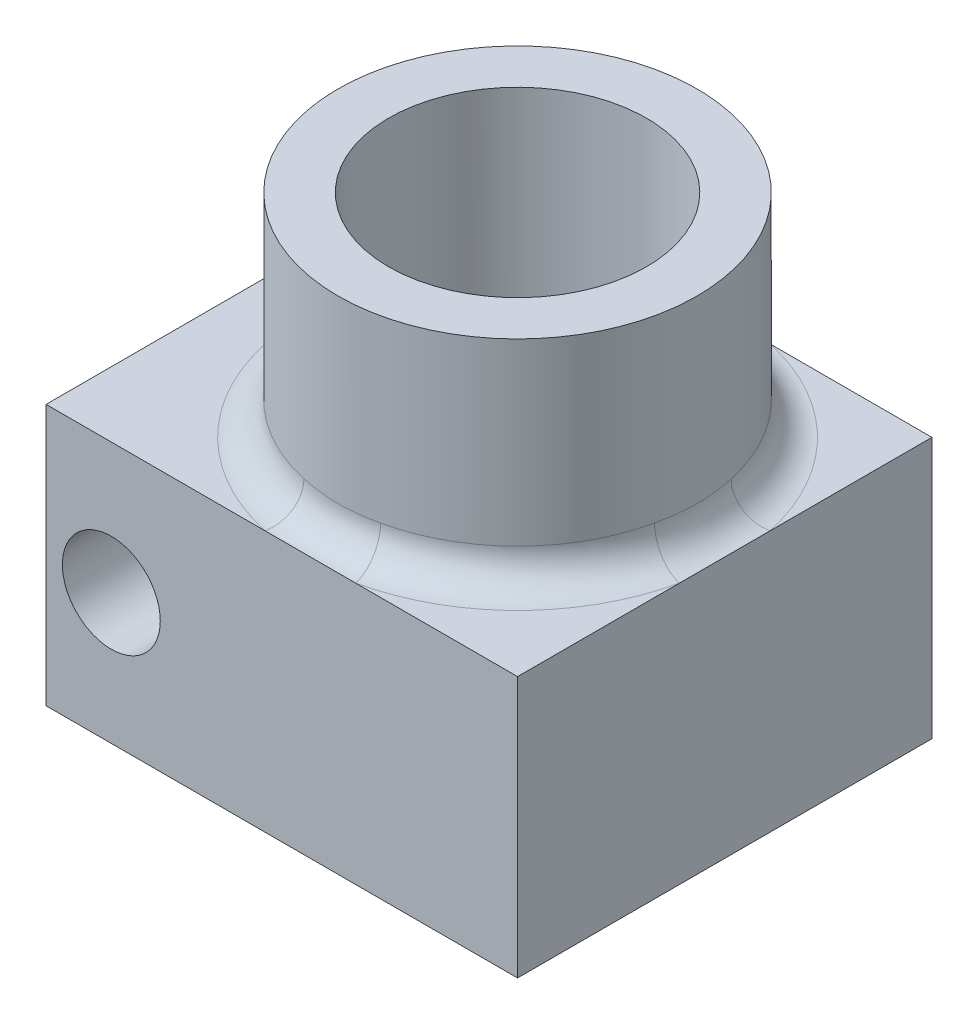
SolidWorks part; units mm, degrees
material "AISI 1020"
ref_plane "Front Plane" through (0, 0, 0) normal (0, 0, 1) x (1, 0, 0)
ref_plane "Top Plane" through (0, 0, 0) normal (0, 1, 0) x (1, 0, 0)
ref_plane "Right Plane" through (0, 0, 0) normal (1, 0, 0) x (0, 0, -1)
sketch "Sketch1" plane through (0, 0, 0) normal (0, 1, 0) x (1, 0, 0)
  line L0 (4.053, -4.2372) -> (-8.647, -4.2372) construction
  line L2 (-8.647, 8.4628) -> (16.753, 8.4628)
  line L4 (16.753, -16.9372) -> (-8.647, -16.9372)
  line L6 (-8.647, -16.9372) -> (-10.397, -16.9372)
  line L8 (-10.397, 8.4628) -> (-8.647, 8.4628)
  line L12 (16.753, 8.4628) -> (16.753, -16.9372)
  line L13 (-10.397, -16.9372) -> (-12.147, -16.9372)
  line L14 (-12.147, -16.9372) -> (-12.147, 8.4628)
  line L15 (-12.147, 8.4628) -> (-10.397, 8.4628)
  arc A0 (1.7659, 3.3245) -> (1.8335, 2.4017) centre (3.6444, 2.9983) ccw
  arc A1 (1.8335, 2.4017) -> (1.4858, 2.2751) centre (4.053, -4.2372) ccw
  arc A2 (1.4858, 2.2751) -> (0.9444, 3.0255) centre (-0.285, 1.5682) ccw
  arc A3 (0.9444, 3.0255) -> (0.4875, 2.8125) centre (4.053, -4.2372) ccw
  arc A4 (0.4875, 2.8125) -> (0.7144, 1.9154) centre (2.3942, 2.8175) ccw
  arc A5 (0.7144, 1.9154) -> (0.3939, 1.7304) centre (4.053, -4.2372) ccw
  arc A6 (0.3939, 1.7304) -> (-0.2695, 2.3754) centre (-1.2272, 0.7267) ccw
  arc A7 (-0.2695, 2.3754) -> (-0.6825, 2.0863) centre (4.053, -4.2372) ccw
  arc A8 (-0.6825, 2.0863) -> (-0.3032, 1.2422) centre (1.1944, 2.4223) ccw
  arc A9 (-0.3032, 1.2422) -> (-0.5867, 1.0043) centre (4.053, -4.2372) ccw
  arc A10 (-0.5867, 1.0043) -> (-1.3521, 1.5243) centre (-2.0089, -0.2656) ccw
  arc A11 (-1.3521, 1.5243) -> (-1.7086, 1.1679) centre (4.053, -4.2372) ccw
  arc A12 (-1.7086, 1.1679) -> (-1.1885, 0.4025) centre (0.0814, 1.8247) ccw
  arc A13 (-1.1885, 0.4025) -> (-1.4264, 0.119) centre (4.053, -4.2372) ccw
  arc A14 (-1.4264, 0.119) -> (-2.2705, 0.4982) centre (-2.6065, -1.3786) ccw
  arc A15 (-2.2705, 0.4982) -> (-2.5596, 0.0853) centre (4.053, -4.2372) ccw
  arc A16 (-2.5596, 0.0853) -> (-1.9146, -0.5782) centre (-0.9109, 1.0429) ccw
  arc A17 (-1.9146, -0.5782) -> (-2.0996, -0.8986) centre (4.053, -4.2372) ccw
  arc A18 (-2.0996, -0.8986) -> (-2.9967, -0.6718) centre (-3.0017, -2.5784) ccw
  arc A19 (-2.9967, -0.6718) -> (-3.2098, -1.1286) centre (4.053, -4.2372) ccw
  arc A20 (-3.2098, -1.1286) -> (-2.4593, -1.67) centre (-1.7524, 0.1008) ccw
  arc A21 (-2.4593, -1.67) -> (-2.5859, -2.0178) centre (4.053, -4.2372) ccw
  arc A22 (-2.5859, -2.0178) -> (-3.5087, -1.9501) centre (-3.1826, -3.8286) ccw
  arc A23 (-3.5087, -1.9501) -> (-3.6392, -2.437) centre (4.053, -4.2372) ccw
  arc A24 (-3.6392, -2.437) -> (-2.8062, -2.8398) centre (-2.4175, -0.9732) ccw
  arc A25 (-2.8062, -2.8398) -> (-2.8704, -3.2043) centre (4.053, -4.2372) ccw
  arc A26 (-2.8704, -3.2043) -> (-3.791, -3.2979) centre (-3.1436, -5.0913) ccw
  arc A27 (-3.791, -3.2979) -> (-3.8349, -3.8001) centre (4.053, -4.2372) ccw
  arc A28 (-3.8349, -3.8001) -> (-2.9446, -4.0521) centre (-2.8859, -2.1464) ccw
  arc A29 (-2.9446, -4.0521) -> (-2.9446, -4.4222) centre (4.053, -4.2372) ccw
  arc A30 (-2.9446, -4.4222) -> (-3.8349, -4.6743) centre (-2.8859, -6.328) ccw
  arc A31 (-3.8349, -4.6743) -> (-3.791, -5.1764) centre (4.053, -4.2372) ccw
  arc A32 (-3.791, -5.1764) -> (-2.8704, -5.2701) centre (-3.1436, -3.3831) ccw
  arc A33 (-2.8704, -5.2701) -> (-2.8062, -5.6345) centre (4.053, -4.2372) ccw
  arc A34 (-2.8062, -5.6345) -> (-3.6392, -6.0374) centre (-2.4175, -7.5011) ccw
  arc A35 (-3.6392, -6.0374) -> (-3.5087, -6.5243) centre (4.053, -4.2372) ccw
  arc A36 (-3.5087, -6.5243) -> (-2.5859, -6.4566) centre (-3.1826, -4.6457) ccw
  arc A37 (-2.5859, -6.4566) -> (-2.4593, -6.8044) centre (4.053, -4.2372) ccw
  arc A38 (-2.4593, -6.8044) -> (-3.2098, -7.3457) centre (-1.7524, -8.5751) ccw
  arc A39 (-3.2098, -7.3457) -> (-2.9967, -7.8026) centre (4.053, -4.2372) ccw
  arc A40 (-2.9967, -7.8026) -> (-2.0996, -7.5757) centre (-3.0017, -5.8959) ccw
  arc A41 (-2.0996, -7.5757) -> (-1.9146, -7.8962) centre (4.053, -4.2372) ccw
  arc A42 (-1.9146, -7.8962) -> (-2.5596, -8.5597) centre (-0.9109, -9.5173) ccw
  arc A43 (-2.5596, -8.5597) -> (-2.2705, -8.9726) centre (4.053, -4.2372) ccw
  arc A44 (-2.2705, -8.9726) -> (-1.4264, -8.5934) centre (-2.6065, -7.0958) ccw
  arc A45 (-1.4264, -8.5934) -> (-1.1885, -8.8769) centre (4.053, -4.2372) ccw
  arc A46 (-1.1885, -8.8769) -> (-1.7086, -9.6423) centre (0.0814, -10.299) ccw
  arc A47 (-1.7086, -9.6423) -> (-1.3521, -9.9987) centre (4.053, -4.2372) ccw
  arc A48 (-1.3521, -9.9987) -> (-0.5867, -9.4787) centre (-2.0089, -8.2087) ccw
  arc A49 (-0.5867, -9.4787) -> (-0.3032, -9.7166) centre (4.053, -4.2372) ccw
  arc A50 (-0.3032, -9.7166) -> (-0.6825, -10.5606) centre (1.1944, -10.8966) ccw
  arc A51 (-0.6825, -10.5606) -> (-0.2695, -10.8498) centre (4.053, -4.2372) ccw
  arc A52 (-0.2695, -10.8498) -> (0.3939, -10.2047) centre (-1.2272, -9.201) ccw
  arc A53 (0.3939, -10.2047) -> (0.7144, -10.3898) centre (4.053, -4.2372) ccw
  arc A54 (0.7144, -10.3898) -> (0.4875, -11.2868) centre (2.3942, -11.2918) ccw
  arc A55 (0.4875, -11.2868) -> (0.9444, -11.4999) centre (4.053, -4.2372) ccw
  arc A56 (0.9444, -11.4999) -> (1.4858, -10.7494) centre (-0.285, -10.0425) ccw
  arc A57 (1.4858, -10.7494) -> (1.8335, -10.876) centre (4.053, -4.2372) ccw
  arc A58 (1.8335, -10.876) -> (1.7659, -11.7989) centre (3.6444, -11.4727) ccw
  arc A59 (1.7659, -11.7989) -> (2.2528, -11.9293) centre (4.053, -4.2372) ccw
  arc A60 (2.2528, -11.9293) -> (2.6556, -11.0963) centre (0.789, -10.7076) ccw
  arc A61 (2.6556, -11.0963) -> (3.0201, -11.1606) centre (4.053, -4.2372) ccw
  arc A62 (3.0201, -11.1606) -> (3.1137, -12.0811) centre (4.9071, -11.4337) ccw
  arc A63 (3.1137, -12.0811) -> (3.6159, -12.1251) centre (4.053, -4.2372) ccw
  arc A64 (3.6159, -12.1251) -> (3.8679, -11.2347) centre (1.9622, -11.1761) ccw
  arc A65 (3.8679, -11.2347) -> (4.238, -11.2347) centre (4.053, -4.2372) ccw
  arc A66 (4.238, -11.2347) -> (4.49, -12.1251) centre (6.1437, -11.1761) ccw
  arc A67 (4.49, -12.1251) -> (4.9922, -12.0811) centre (4.053, -4.2372) ccw
  arc A68 (4.9922, -12.0811) -> (5.0858, -11.1606) centre (3.1989, -11.4337) ccw
  arc A69 (5.0858, -11.1606) -> (5.4503, -11.0963) centre (4.053, -4.2372) ccw
  arc A70 (5.4503, -11.0963) -> (5.8531, -11.9293) centre (7.3169, -10.7076) ccw
  arc A71 (5.8531, -11.9293) -> (6.34, -11.7989) centre (4.053, -4.2372) ccw
  arc A72 (6.34, -11.7989) -> (6.2724, -10.876) centre (4.4615, -11.4727) ccw
  arc A73 (6.2724, -10.876) -> (6.6201, -10.7494) centre (4.053, -4.2372) ccw
  arc A74 (6.6201, -10.7494) -> (7.1615, -11.4999) centre (8.3909, -10.0425) ccw
  arc A75 (7.1615, -11.4999) -> (7.6184, -11.2868) centre (4.053, -4.2372) ccw
  arc A76 (7.6184, -11.2868) -> (7.3915, -10.3898) centre (5.7117, -11.2918) ccw
  arc A77 (7.3915, -10.3898) -> (7.712, -10.2047) centre (4.053, -4.2372) ccw
  arc A78 (7.712, -10.2047) -> (8.3754, -10.8498) centre (9.3331, -9.201) ccw
  arc A79 (8.3754, -10.8498) -> (8.7884, -10.5606) centre (4.053, -4.2372) ccw
  arc A80 (8.7884, -10.5606) -> (8.4091, -9.7166) centre (6.9115, -10.8966) ccw
  arc A81 (8.4091, -9.7166) -> (8.6926, -9.4787) centre (4.053, -4.2372) ccw
  arc A82 (8.6926, -9.4787) -> (9.458, -9.9987) centre (10.1148, -8.2087) ccw
  arc A83 (9.458, -9.9987) -> (9.8145, -9.6423) centre (4.053, -4.2372) ccw
  arc A84 (9.8145, -9.6423) -> (9.2944, -8.8769) centre (8.0245, -10.299) ccw
  arc A85 (9.2944, -8.8769) -> (9.5323, -8.5934) centre (4.053, -4.2372) ccw
  arc A86 (9.5323, -8.5934) -> (10.3764, -8.9726) centre (10.7124, -7.0958) ccw
  arc A87 (10.3764, -8.9726) -> (10.6655, -8.5597) centre (4.053, -4.2372) ccw
  arc A88 (10.6655, -8.5597) -> (10.0205, -7.8962) centre (9.0168, -9.5173) ccw
  arc A89 (10.0205, -7.8962) -> (10.2055, -7.5757) centre (4.053, -4.2372) ccw
  arc A90 (10.2055, -7.5757) -> (11.1026, -7.8026) centre (11.1076, -5.8959) ccw
  arc A91 (11.1026, -7.8026) -> (11.3157, -7.3457) centre (4.053, -4.2372) ccw
  arc A92 (11.3157, -7.3457) -> (10.5652, -6.8044) centre (9.8583, -8.5751) ccw
  arc A93 (10.5652, -6.8044) -> (10.6918, -6.4566) centre (4.053, -4.2372) ccw
  arc A94 (10.6918, -6.4566) -> (11.6146, -6.5243) centre (11.2885, -4.6457) ccw
  arc A95 (11.6146, -6.5243) -> (11.7451, -6.0374) centre (4.053, -4.2372) ccw
  arc A96 (11.7451, -6.0374) -> (10.9121, -5.6345) centre (10.5234, -7.5011) ccw
  arc A97 (10.9121, -5.6345) -> (10.9763, -5.2701) centre (4.053, -4.2372) ccw
  arc A98 (10.9763, -5.2701) -> (11.8969, -5.1764) centre (11.2495, -3.3831) ccw
  arc A99 (11.8969, -5.1764) -> (11.9409, -4.6743) centre (4.053, -4.2372) ccw
  arc A100 (11.9409, -4.6743) -> (11.0505, -4.4222) centre (10.9918, -6.328) ccw
  arc A101 (11.0505, -4.4222) -> (11.0505, -4.0521) centre (4.053, -4.2372) ccw
  arc A102 (11.0505, -4.0521) -> (11.9409, -3.8001) centre (10.9918, -2.1464) ccw
  arc A103 (11.9409, -3.8001) -> (11.8969, -3.2979) centre (4.053, -4.2372) ccw
  arc A104 (11.8969, -3.2979) -> (10.9763, -3.2043) centre (11.2495, -5.0913) ccw
  arc A105 (10.9763, -3.2043) -> (10.9121, -2.8398) centre (4.053, -4.2372) ccw
  arc A106 (10.9121, -2.8398) -> (11.7451, -2.437) centre (10.5234, -0.9732) ccw
  arc A107 (11.7451, -2.437) -> (11.6146, -1.9501) centre (4.053, -4.2372) ccw
  arc A108 (11.6146, -1.9501) -> (10.6918, -2.0178) centre (11.2885, -3.8286) ccw
  arc A109 (10.6918, -2.0178) -> (10.5652, -1.67) centre (4.053, -4.2372) ccw
  arc A110 (10.5652, -1.67) -> (11.3157, -1.1286) centre (9.8583, 0.1008) ccw
  arc A111 (11.3157, -1.1286) -> (11.1026, -0.6718) centre (4.053, -4.2372) ccw
  arc A112 (11.1026, -0.6718) -> (10.2055, -0.8986) centre (11.1076, -2.5784) ccw
  arc A113 (10.2055, -0.8986) -> (10.0205, -0.5782) centre (4.053, -4.2372) ccw
  arc A114 (10.0205, -0.5782) -> (10.6655, 0.0853) centre (9.0168, 1.0429) ccw
  arc A115 (10.6655, 0.0853) -> (10.3764, 0.4982) centre (4.053, -4.2372) ccw
  arc A116 (10.3764, 0.4982) -> (9.5323, 0.119) centre (10.7124, -1.3786) ccw
  arc A117 (9.5323, 0.119) -> (9.2944, 0.4025) centre (4.053, -4.2372) ccw
  arc A118 (9.2944, 0.4025) -> (9.8145, 1.1679) centre (8.0245, 1.8247) ccw
  arc A119 (9.8145, 1.1679) -> (9.458, 1.5243) centre (4.053, -4.2372) ccw
  arc A120 (9.458, 1.5243) -> (8.6926, 1.0043) centre (10.1148, -0.2656) ccw
  arc A121 (8.6926, 1.0043) -> (8.4091, 1.2422) centre (4.053, -4.2372) ccw
  arc A122 (8.4091, 1.2422) -> (8.7884, 2.0863) centre (6.9115, 2.4223) ccw
  arc A123 (8.7884, 2.0863) -> (8.3754, 2.3754) centre (4.053, -4.2372) ccw
  arc A124 (8.3754, 2.3754) -> (7.712, 1.7304) centre (9.3331, 0.7267) ccw
  arc A125 (7.712, 1.7304) -> (7.3915, 1.9154) centre (4.053, -4.2372) ccw
  arc A126 (7.3915, 1.9154) -> (7.6184, 2.8125) centre (5.7117, 2.8175) ccw
  arc A127 (7.6184, 2.8125) -> (7.1615, 3.0255) centre (4.053, -4.2372) ccw
  arc A128 (7.1615, 3.0255) -> (6.6201, 2.2751) centre (8.3909, 1.5682) ccw
  arc A129 (6.6201, 2.2751) -> (6.2724, 2.4017) centre (4.053, -4.2372) ccw
  arc A130 (6.2724, 2.4017) -> (6.34, 3.3245) centre (4.4615, 2.9983) ccw
  arc A131 (6.34, 3.3245) -> (5.8531, 3.455) centre (4.053, -4.2372) ccw
  arc A132 (5.8531, 3.455) -> (5.4503, 2.6219) centre (7.3169, 2.2332) ccw
  arc A133 (5.4503, 2.6219) -> (5.0858, 2.6862) centre (4.053, -4.2372) ccw
  arc A134 (5.0858, 2.6862) -> (4.9922, 3.6068) centre (3.1989, 2.9594) ccw
  arc A135 (4.9922, 3.6068) -> (4.49, 3.6507) centre (4.053, -4.2372) ccw
  arc A136 (4.49, 3.6507) -> (4.238, 2.7604) centre (6.1437, 2.7017) ccw
  arc A137 (4.238, 2.7604) -> (3.8679, 2.7604) centre (4.053, -4.2372) ccw
  arc A138 (3.8679, 2.7604) -> (3.6159, 3.6507) centre (1.9622, 2.7017) ccw
  arc A139 (3.6159, 3.6507) -> (3.1137, 3.6068) centre (4.053, -4.2372) ccw
  arc A140 (3.1137, 3.6068) -> (3.0201, 2.6862) centre (4.9071, 2.9594) ccw
  arc A141 (3.0201, 2.6862) -> (2.6556, 2.6219) centre (4.053, -4.2372) ccw
  arc A142 (2.6556, 2.6219) -> (2.2528, 3.455) centre (0.789, 2.2332) ccw
  arc A143 (2.2528, 3.455) -> (1.7659, 3.3245) centre (4.053, -4.2372) ccw
extrude "Boss-Extrude1" add sketch "Sketch1" along normal blind 16
sketch "Sketch2" plane through (0, 16, 0) normal (0, 1, 0) x (1, 0, 0)
  circle A0 centre (4.053, -4.2372) radius 7.9
  circle A1 centre (4.053, -4.2372) radius 11
extrude "Boss-Extrude2" add sketch "Sketch2" along normal blind 13
fillet "Fillet1" radius 2 1 edges at (4.053, 16, -6.7628)
sketch "Sketch3" plane through (0, 0, 16.9372) normal (0, 0, 1) x (1, 0, 0)
  line L0 (-12.147, 8) -> (-8.147, 8) construction
  line L1 (-12.147, 16) -> (-12.147, 0) construction
  circle A0 centre (-8.147, 8) radius 3
extrude "Cut-Extrude1" cut sketch "Sketch3" against normal blind 30
